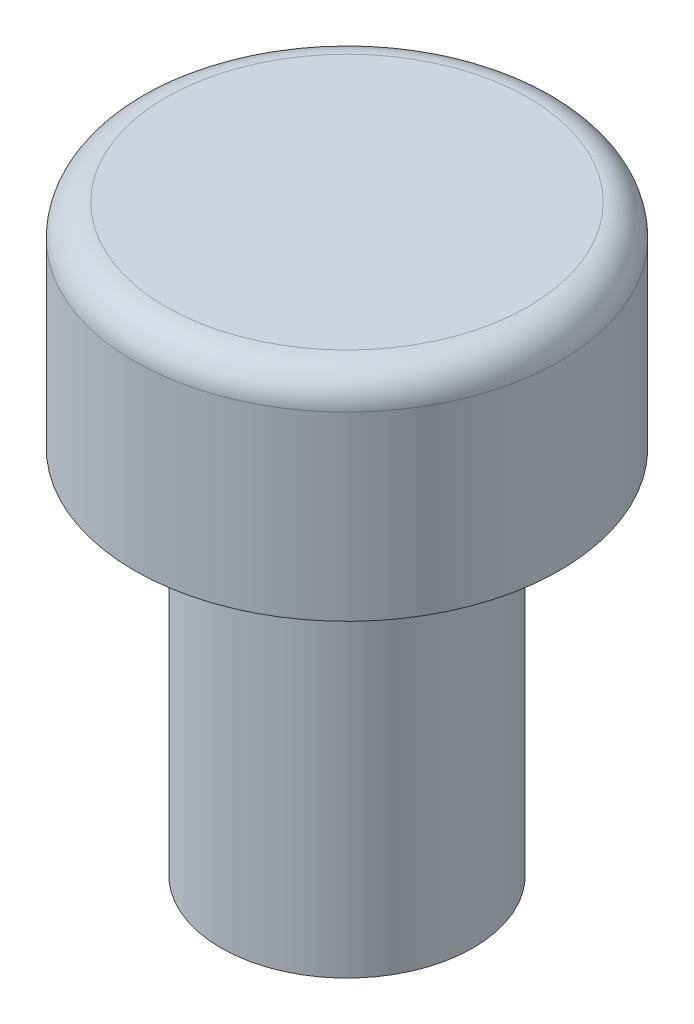
SolidWorks part; units mm, degrees
ref_plane "Front Plane" through (0, 0, 0) normal (0, 0, 1) x (1, 0, 0)
ref_plane "Top Plane" through (0, 0, 0) normal (0, 1, 0) x (1, 0, 0)
ref_plane "Right Plane" through (0, 0, 0) normal (1, 0, 0) x (0, 0, -1)
sketch "Sketch1" plane through (0, 0, 0) normal (0, 0, 1) x (1, 0, 0)
  line L0 (0, 0) -> (0, 37)
  line L1 (0, 37) -> (13.5, 37)
  line L2 (13.5, 37) -> (13.5, 23.5)
  line L3 (13.5, 23.5) -> (8, 23.5)
  line L4 (8, 23.5) -> (8, 0)
  line L5 (8, 0) -> (0, 0)
  dimension "D1" = 37
  dimension "D2" = 13.5
  dimension "D3" = 13.5
  dimension "D4" = 8
revolve "Revolve1" add sketch "Sketch1" angle 360 about L0
fillet "Fillet1" radius 2 1 edges at (0, 37, -13.5)
